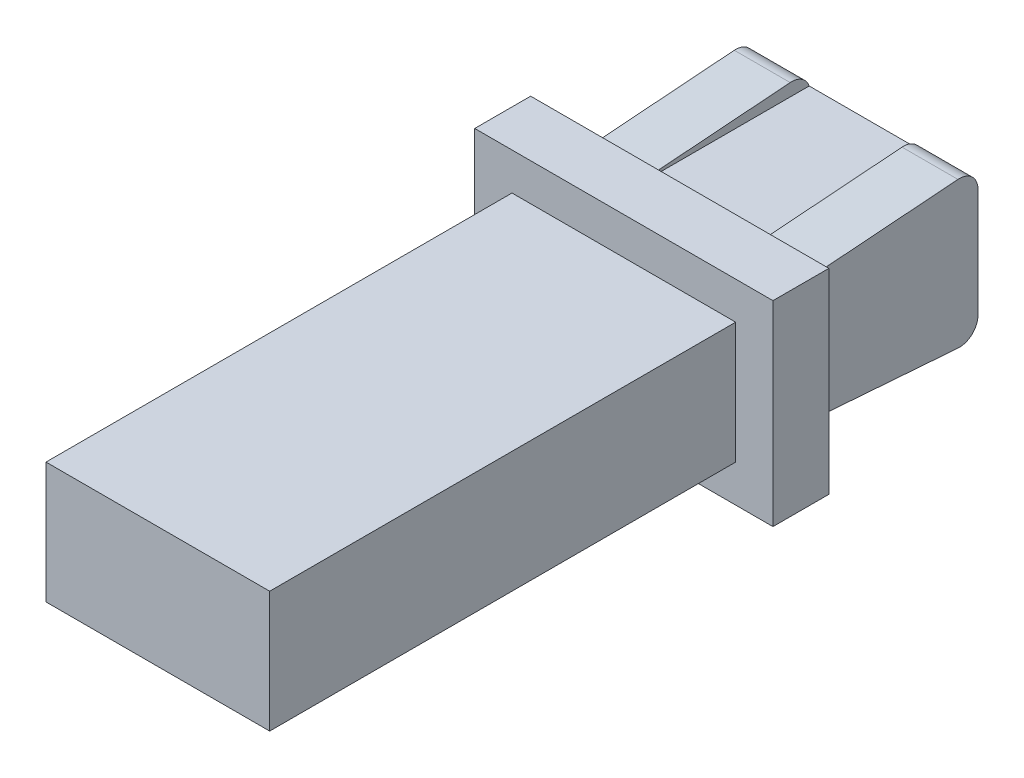
SolidWorks part; units mm, degrees
ref_plane "Front Plane" through (0, 0, 0) normal (0, 0, 1) x (1, 0, 0)
ref_plane "Top Plane" through (0, 0, 0) normal (0, 1, 0) x (1, 0, 0)
ref_plane "Right Plane" through (0, 0, 0) normal (1, 0, 0) x (0, 0, -1)
sketch "Sketch1" plane through (0, 0, 0) normal (0, 0, 1) x (1, 0, 0)
  line L1 (-6, 3.25) -> (6, 3.25)
  line L2 (-6, 3.25) -> (-6, -3.25)
  line L3 (-6, -3.25) -> (6, -3.25)
  line L4 (6, 3.25) -> (6, -3.25)
  line L5 (-6, 3.25) -> (6, -3.25) construction
  line L6 (-6, -3.25) -> (6, 3.25) construction
  point P0 (0, 0)
  dimension "D1" = 12
  dimension "D2" = 6.5
extrude "Boss-Extrude1" add sketch "Sketch1" along normal blind 10
sketch "Sketch2" plane through (0, 0, 10) normal (0, 0, 1) x (1, 0, 0)
  line L8 (8, -5.25) -> (8, 5.25)
  line L9 (8, 5.25) -> (-8, 5.25)
  line L10 (-8, 5.25) -> (-8, -5.25)
  line L11 (-8, -5.25) -> (8, -5.25)
  line L12 (8, -5.25) -> (8, 5.25)
  line L13 (8, 5.25) -> (-8, 5.25)
  line L14 (-8, 5.25) -> (-8, -5.25)
  line L15 (-8, -5.25) -> (8, -5.25)
  dimension "D1" = 2
extrude "Boss-Extrude2" add sketch "Sketch2" along normal blind 3
sketch "Sketch3" plane through (0, 0, 13) normal (0, 0, 1) x (1, 0, 0)
  line L8 (-6, -3.25) -> (6, -3.25)
  line L9 (6, -3.25) -> (6, 3.25)
  line L10 (6, 3.25) -> (-6, 3.25)
  line L11 (-6, 3.25) -> (-6, -3.25)
  line L12 (-6, -3.25) -> (6, -3.25)
  line L13 (6, -3.25) -> (6, 3.25)
  line L14 (6, 3.25) -> (-6, 3.25)
  line L15 (-6, 3.25) -> (-6, -3.25)
  dimension "D1" = 2
extrude "Boss-Extrude3" add sketch "Sketch3" along normal blind 25
sketch "Sketch4" plane through (6, 0, 0) normal (1, 0, 0) x (0, 0, -1)
  line L4 (-10, 3.25) -> (0, 4)
  line L5 (0, 4) -> (0, 3.25)
  line L6 (-10, -3.25) -> (0, -4)
  line L7 (0, -4) -> (0, -3.25)
  line L8 (0, -3.25) -> (0, 3.25)
  line L9 (0, 3.25) -> (-10, 3.25)
  line L10 (-10, 3.25) -> (-10, -3.25)
  line L11 (-10, -3.25) -> (0, -3.25)
  line L13 (0, 3.25) -> (-10, 3.25)
  line L15 (-10, -3.25) -> (0, -3.25)
  dimension "D2" = 0.75
  dimension "D1" = 0
extrude "Boss-Extrude4" add sketch "Sketch4" against normal up to surface (12 mm away) up to face at (-6, 0, 5)
fillet "Fillet1" radius 1 2 edges at (0, -4, 0) (0, 4, 0)
sketch "Sketch5" plane through (0, 0, 0) normal (0, 0, -1) x (-1, 0, 0)
  line L0 (6, 3.9222) -> (-6, 3.9222) construction
  line L1 (-3, 3.9222) -> (3, 3.9222)
  line L2 (-3, 3.9222) -> (-3, 3.25)
  line L3 (-3, 3.25) -> (3, 3.25)
  line L4 (3, 3.9222) -> (3, 3.25)
  line L5 (-6, -3.9222) -> (6, -3.9222) construction
  line L6 (-3, -3.9222) -> (3, -3.9222)
  line L7 (-3, -3.9222) -> (-3, -3.25)
  line L8 (-3, -3.25) -> (3, -3.25)
  line L9 (3, -3.9222) -> (3, -3.25)
  point P12 (0, 3.25)
  dimension "D1" = 6
  dimension "D2" = 3.25
extrude "Cut-Extrude1" cut sketch "Sketch5" against normal up to next
